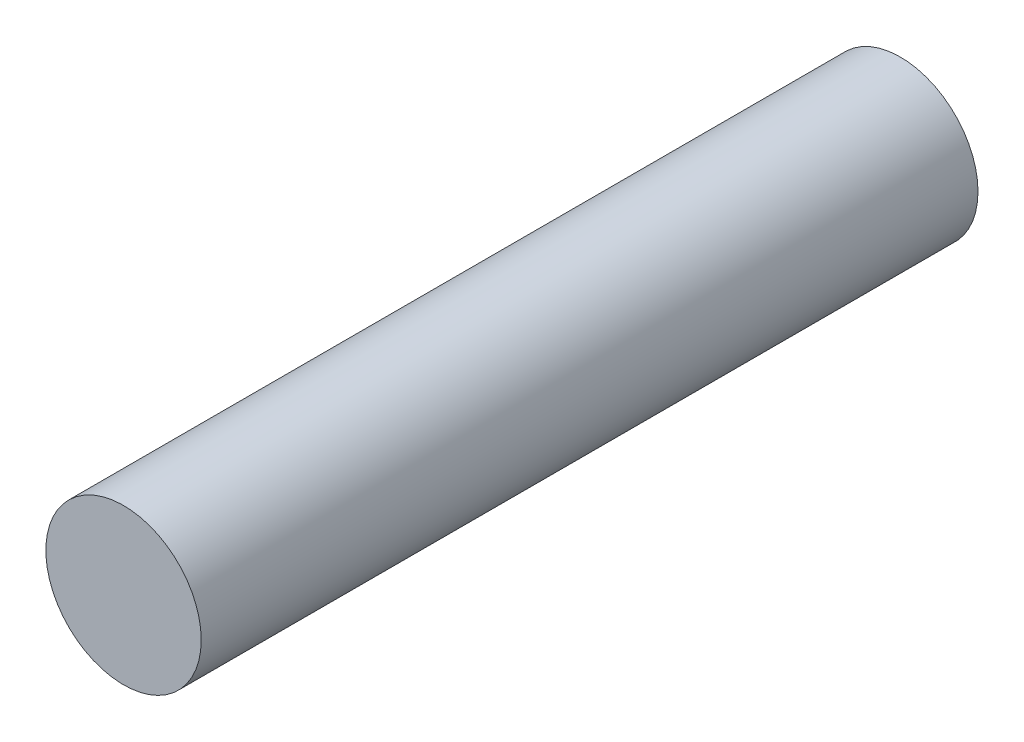
SolidWorks part; units mm, degrees
ref_plane "Front Plane" through (0, 0, 0) normal (0, 0, 1) x (1, 0, 0)
ref_plane "Top Plane" through (0, 0, 0) normal (0, 1, 0) x (1, 0, 0)
ref_plane "Right Plane" through (0, 0, 0) normal (1, 0, 0) x (0, 0, -1)
sketch "Sketch1" plane through (0, 0, 0) normal (0, 0, 1) x (1, 0, 0)
  circle A0 centre (0, 0) radius 0.5
extrude "Boss-Extrude1" add sketch "Sketch1" along normal blind 5
